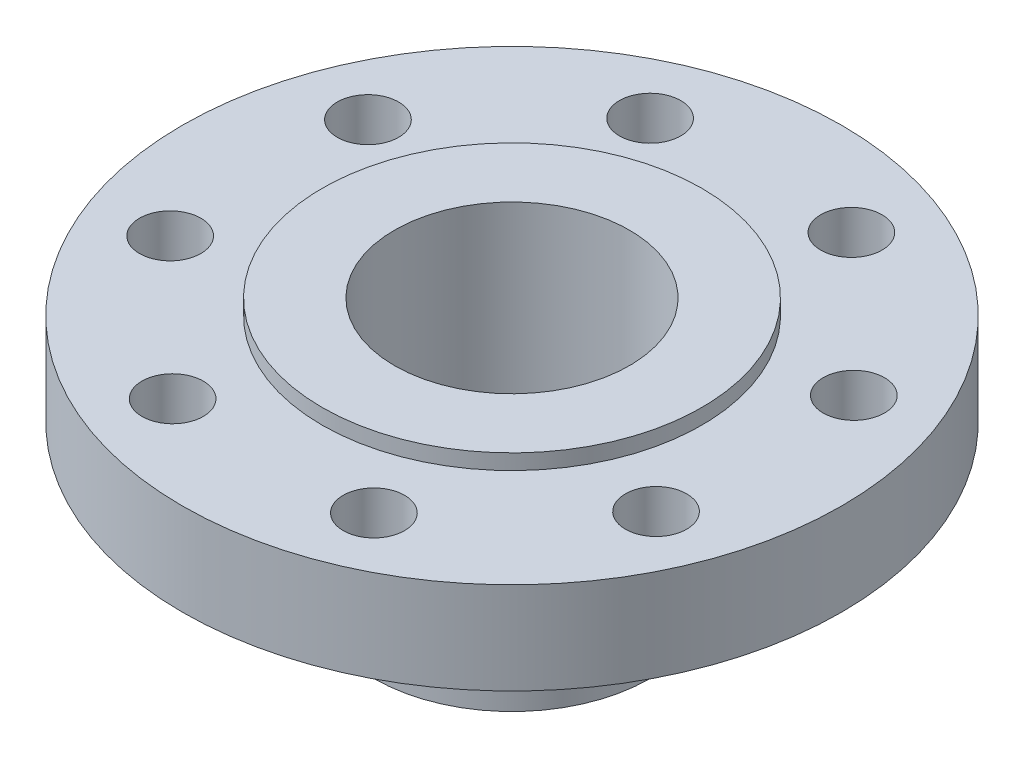
SolidWorks part; units mm, degrees
ref_plane "Front Plane" through (0, 0, 0) normal (0, 0, 1) x (1, 0, 0)
ref_plane "Top Plane" through (0, 0, 0) normal (0, 1, 0) x (1, 0, 0)
ref_plane "Right Plane" through (0, 0, 0) normal (1, 0, 0) x (0, 0, -1)
sketch "Sketch1" plane through (0, 0, 0) normal (0, 0, 1) x (1, 0, 0)
  line L0 (0, 145.4262) -> (0, -147.4014) construction
  line L1 (48.64, 0) -> (48.64, 107.95)
  line L2 (48.64, 107.95) -> (78.615, 107.95)
  line L3 (78.615, 107.95) -> (78.615, 101.6)
  line L4 (78.615, 101.6) -> (136.525, 101.6)
  line L5 (136.525, 101.6) -> (136.525, 63.5)
  line L6 (136.525, 63.5) -> (78.615, 63.5)
  line L7 (78.615, 63.5) -> (57.15, 11.29)
  line L8 (57.15, 11.29) -> (57.15, 0)
  line L9 (57.15, 0) -> (48.64, 0)
  point P7 (78.615, 63.5)
  point P13 (0, 0)
  dimension "D1" = 97.28
  dimension "D2" = 157.23
  dimension "D3" = 273.05
  dimension "D4" = 114.3
  dimension "D5" = 11.29
  dimension "D6" = 52.21
  dimension "D7" = 38.1
  dimension "D8" = 6.35
revolve "Revolve1" add sketch "Sketch1" angle 360 about L0
sketch "Sketch2" plane through (0, 101.6, 0) normal (0, 1, 0) x (1, 0, 0)
  line L0 (0, 0) -> (0, 149.6558) construction
  line L1 (0, 0) -> (-42.1794, 99.3685) construction
  line L2 (0, 0) -> (-100.0895, 40.4388) construction
  circle A0 centre (0, 0) radius 107.95 construction
  circle A1 centre (-42.1794, 99.3685) radius 12.7
  circle A2 centre (40.4388, 100.0895) radius 12.7
  circle A3 centre (99.3685, 42.1794) radius 12.7
  circle A4 centre (100.0895, -40.4388) radius 12.7
  circle A5 centre (42.1794, -99.3685) radius 12.7
  circle A6 centre (-40.4388, -100.0895) radius 12.7
  circle A7 centre (-99.3685, -42.1794) radius 12.7
  circle A8 centre (-100.0895, 40.4388) radius 12.7
  point P5 (-100.0895, 42.1794)
  point P24 (0, 0)
  dimension "D1" = 215.9
  dimension "D2" = 25.4
  dimension "D3" = 23
  dimension "D5" = 45
  dimension "D4" = 8
extrude "Cut-Extrude1" cut sketch "Sketch2" against normal blind 53
